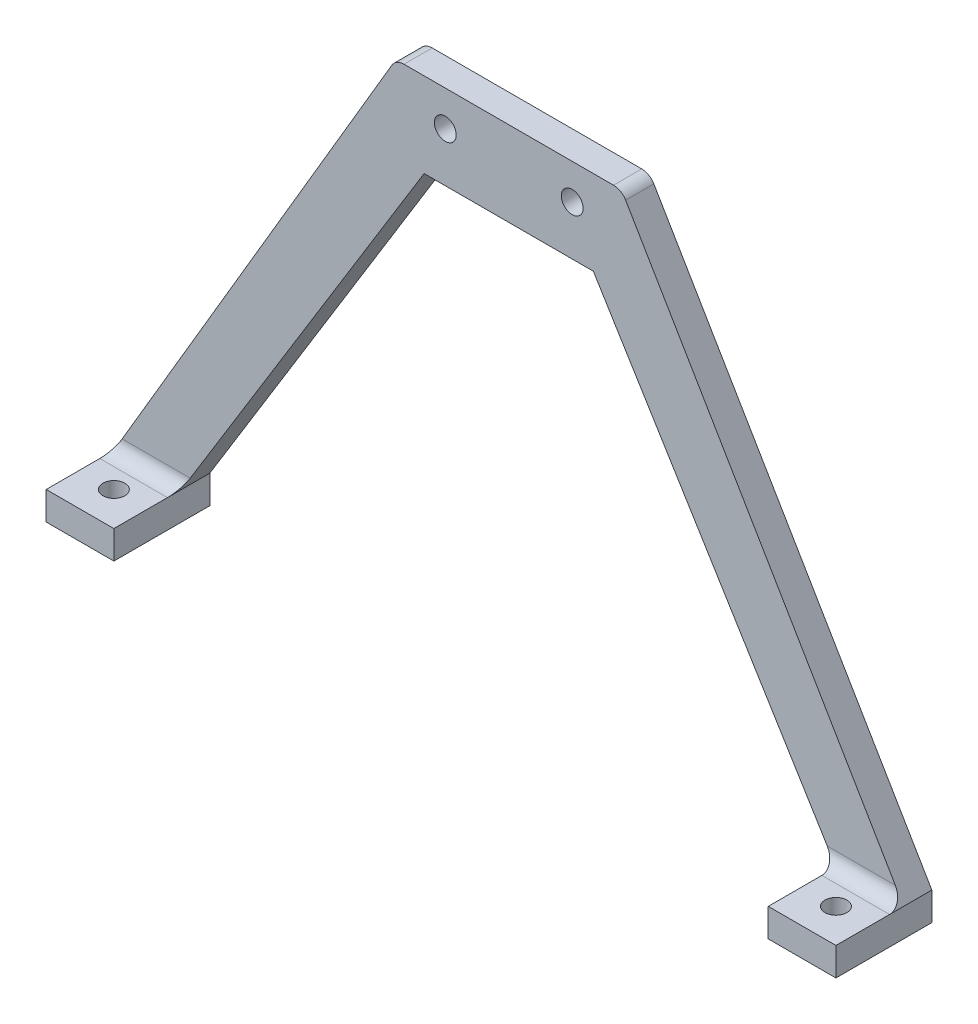
SolidWorks part; units mm, degrees
ref_plane "Front Plane" through (0, 0, 0) normal (0, 0, 1) x (1, 0, 0)
ref_plane "Top Plane" through (0, 0, 0) normal (0, 1, 0) x (1, 0, 0)
ref_plane "Right Plane" through (0, 0, 0) normal (1, 0, 0) x (0, 0, -1)
sketch "Sketch1" plane through (0, 0, 0) normal (0, 0, 1) x (1, 0, 0)
  line L1 (0, 0) -> (112, 0)
  line L2 (0, 0) -> (0, -72)
  line L3 (0, -72) -> (112, -72)
  line L4 (112, 0) -> (112, -72)
  dimension "D1" = 112
  dimension "D2" = 72
extrude "Boss-Extrude1" add sketch "Sketch1" along normal blind 4
sketch "Sketch2" plane through (0, 0, 4) normal (0, 0, 1) x (1, 0, 0)
  line L0 (0, -72) -> (112, -72) construction
  line L1 (0, -72) -> (9.6, -72)
  line L2 (0, -72) -> (0, -68)
  line L3 (0, -68) -> (9.6, -68)
  line L4 (9.6, -72) -> (9.6, -68)
  line L6 (102.4, -72) -> (112, -72)
  line L7 (102.4, -72) -> (102.4, -68)
  line L8 (102.4, -68) -> (112, -68)
  line L9 (112, -72) -> (112, -68)
  line L10 (51.2, -72) -> (60.8, -72)
  line L11 (51.2, -72) -> (51.2, -68)
  line L12 (51.2, -68) -> (60.8, -68)
  line L13 (60.8, -72) -> (60.8, -68)
  dimension "D4" = 9.6
  dimension "D1" = 9.6
  dimension "D5" = 9.6
  dimension "D6" = 51.2
  dimension "D7" = 4
  dimension "D8" = 4
  dimension "D9" = 4
  dimension "D2" = 102.4
extrude "Boss-Extrude2" add sketch "Sketch2" along normal blind 9.6
sketch "Sketch3" plane through (0, -68, 0) normal (0, 1, 0) x (1, 0, 0)
  line L0 (9.6, -13.6) -> (0, -13.6) construction
  line L1 (60.8, -13.6) -> (51.2, -13.6) construction
  line L2 (112, -13.6) -> (102.4, -13.6) construction
  line L3 (0, -13.6) -> (0, -4) construction
  line L4 (51.2, -13.6) -> (51.2, -4) construction
  line L5 (102.4, -13.6) -> (102.4, -4) construction
  circle A0 centre (4.8, -8.8) radius 1.55
  circle A1 centre (56, -8.8) radius 1.55
  circle A2 centre (107.2, -8.8) radius 1.55
  dimension "D1" = 3.1
  dimension "D2" = 3.1
  dimension "D3" = 3.1
  dimension "D4" = 4.8
  dimension "D5" = 4.8
  dimension "D6" = 4.8
  dimension "D7" = 4.8
  dimension "D8" = 4.8
  dimension "D9" = 4.8
extrude "Cut-Extrude1" cut sketch "Sketch3" against normal blind 9.6
sketch "Sketch4" plane through (0, 0, 4) normal (0, 0, 1) x (1, 0, 0)
  line L0 (112, 0) -> (0, 0) construction
  circle A0 centre (47, -5) radius 1.55
  circle A1 centre (65, -5) radius 1.55
  circle A2 centre (56, -14) radius 1.55
  point P8 (56, 0)
  dimension "D6" = 3.1
  dimension "D7" = 3.1
  dimension "D8" = 3.1
  dimension "D1" = 18
  dimension "D2" = 9
  dimension "D3" = 9
  dimension "D4" = 5
  dimension "D5" = 5
extrude "Cut-Extrude2" cut sketch "Sketch4" against normal blind 9.6
sketch "Sketch5" plane through (0, 0, 4) normal (0, 0, 1) x (1, 0, 0)
  line L0 (0, -68) -> (0, 0)
  line L1 (0, 0) -> (40, 0)
  line L2 (112, 0) -> (0, 0) construction
  line L3 (40, 0) -> (0, -68)
  line L4 (72, 0) -> (112, -68)
  line L5 (56, 0) -> (56, -7.382) construction
  line L8 (112, 0) -> (72, 0)
  line L9 (112, -68) -> (112, 0)
  dimension "D1" = 40
extrude "Cut-Extrude4" cut sketch "Sketch5" against normal blind 9.6
sketch "Sketch6" plane through (0, 0, 4) normal (0, 0, 1) x (1, 0, 0)
  line L0 (9.6, -68) -> (44, -12)
  line L1 (44, -12) -> (51.2, -68)
  line L2 (51.2, -68) -> (51.2, -72)
  line L3 (51.2, -72) -> (9.6, -72)
  line L4 (9.6, -72) -> (9.6, -68)
  line L5 (56, 0) -> (56, -8.7021) construction
  line L6 (72, 0) -> (40, 0) construction
  line L7 (102.4, -72) -> (102.4, -68)
  line L8 (60.8, -68) -> (60.8, -72)
  line L9 (60.8, -72) -> (102.4, -72)
  line L10 (68, -12) -> (60.8, -68)
  line L11 (102.4, -68) -> (68, -12)
  dimension "D1" = 12
  dimension "D2" = 12
extrude "Cut-Extrude5" cut sketch "Sketch6" against normal blind 9.6
sketch "Sketch7" plane through (0, 0, 4) normal (0, 0, 1) x (1, 0, 0)
  line L0 (44, -12) -> (68, -12)
  line L1 (68, -12) -> (68, -81.9219)
  line L2 (68, -81.9219) -> (38.6283, -80.4697)
  line L3 (38.6283, -80.4697) -> (44, -12)
extrude "Cut-Extrude6" cut sketch "Sketch7" against normal blind 10
fillet "Fillet1" radius 2 2 edges at (107.2, -68, 4) (4.8, -68, 4)
fillet "Fillet2" radius 2 2 edges at (72, 0, 2) (40, 0, 2)
equation "\"D1@Sketch1\"=102.4+9.6"
equation "\"D2@Sketch1\"=0.8*90"
equation "\"D6@Sketch2\"=102.4/2"
equation "\"D2@Sketch3\"=\"D1@Sketch3\""
equation "\"D3@Sketch3\"=\"D1@Sketch3\""
equation "\"D5@Sketch3\"=\"D4@Sketch3\""
equation "\"D6@Sketch3\"=\"D4@Sketch3\""
equation "\"D5@Sketch2\"=\"D4@Sketch2\""
equation "\"D1@Sketch2\"=\"D4@Sketch2\""
equation "\"D7@Sketch3\"=4.8"
equation "\"D8@Sketch3\"=\"D4@Sketch3\""
equation "\"D9@Sketch3\"=\"D4@Sketch3\""
equation "\"D5@Sketch4\"=\"D4@Sketch4\""
